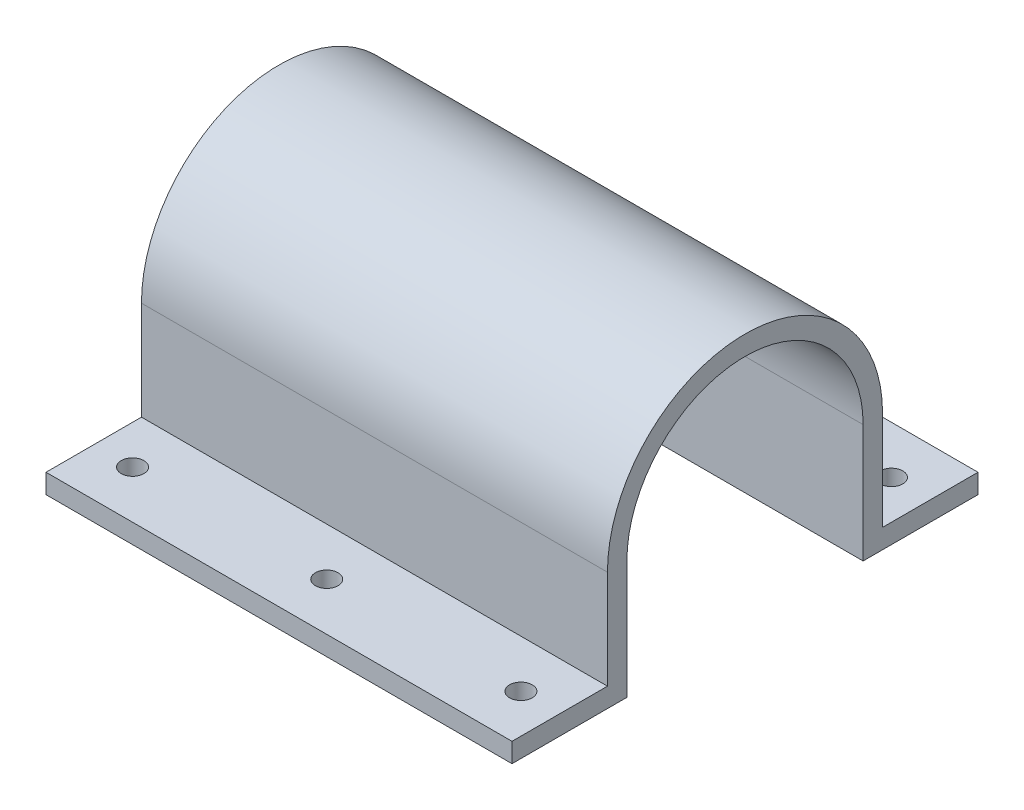
SolidWorks part; units mm, degrees
ref_plane "Front Plane" through (0, 0, 0) normal (0, 0, 1) x (1, 0, 0)
ref_plane "Top Plane" through (0, 0, 0) normal (0, 1, 0) x (1, 0, 0)
ref_plane "Right Plane" through (0, 0, 0) normal (1, 0, 0) x (0, 0, -1)
sketch "Sketch1" plane through (0, 0, 0) normal (1, 0, 0) x (0, 0, -1)
  line L0 (0, -18.25) -> (36, -18.25) construction
  line L1 (0, 0) -> (0, -18.25) construction
  line L2 (18.25, 0) -> (18.25, -18.25)
  line L3 (21.25, 0) -> (21.25, -15.25)
  line L4 (21.25, -15.25) -> (36, -15.25)
  line L5 (36, -15.25) -> (36, -18.25)
  line L6 (36, -18.25) -> (18.25, -18.25)
  line L7 (-36, -15.25) -> (-36, -18.25)
  line L8 (-36, -18.25) -> (-18.25, -18.25)
  line L9 (-21.25, -15.25) -> (-36, -15.25)
  line L10 (-21.25, 0) -> (-21.25, -15.25)
  line L11 (-18.25, 0) -> (-18.25, -18.25)
  arc A0 (18.25, 0) -> (-18.25, 0) centre (0, 0) ccw
  arc A1 (21.25, 0) -> (-21.25, 0) centre (0, 0) ccw
  dimension "D1" = 36.5
  dimension "D2" = 3
  dimension "D3" = 3
  dimension "D4" = 72
extrude "Boss-Extrude1" add sketch "Sketch1" along normal blind 72
sketch "Sketch2" plane through (0, 0, 0) normal (-1, 0, 0) x (0, 0, 1)
  line L0 (-18.25, -18.25) -> (18.25, -18.25)
  line L1 (18.25, -18.25) -> (18.25, 0) construction
  line L2 (-18.25, 0) -> (-18.25, -18.25) construction
  line L3 (18.25, -18.25) -> (18.25, 0)
  line L4 (-18.25, 0) -> (-18.25, -18.25)
  line L5 (0, 0) -> (-15, 0) construction
  line L6 (0, 0) -> (0, -18.25) construction
  arc A0 (18.25, 0) -> (-18.25, 0) centre (0, 0) ccw construction
  arc A1 (18.25, 0) -> (-18.25, 0) centre (0, 0) ccw
  circle A2 centre (0, 0) radius 11.25
  circle A3 centre (-15, 0) radius 1.75
  circle A4 centre (0, 15) radius 1.75
  circle A5 centre (15, 0) radius 1.75
  circle A6 centre (0, -15) radius 1.75
  point P20 (0, 0)
  dimension "D3" = 22.5
  dimension "D5" = 3.5
  dimension "D1" = 90
  dimension "D4" = 15
  dimension "D2" = 4
extrude "Boss-Extrude2" add sketch "Sketch2" against normal blind 3
sketch "Sketch3" plane through (0, -15.25, 0) normal (0, 1, 0) x (1, 0, 0)
  line L0 (0, 0) -> (72, 0) construction
  line L1 (72, -21.25) -> (72, 21.25) construction
  line L2 (0, 28.625) -> (72, 28.625) construction
  line L3 (0, 36) -> (0, 21.25) construction
  line L4 (72, 36) -> (72, 21.25) construction
  circle A0 centre (36, 28.625) radius 1.75
  circle A1 centre (6, 28.625) radius 1.75
  circle A2 centre (66, 28.625) radius 1.75
  circle A3 centre (66, -28.625) radius 1.75
  circle A4 centre (36, -28.625) radius 1.75
  circle A5 centre (6, -28.625) radius 1.75
  dimension "D1" = 3.5
  dimension "D2" = 30
  dimension "D3" = 30
extrude "Cut-Extrude1" cut sketch "Sketch3" against normal through all
